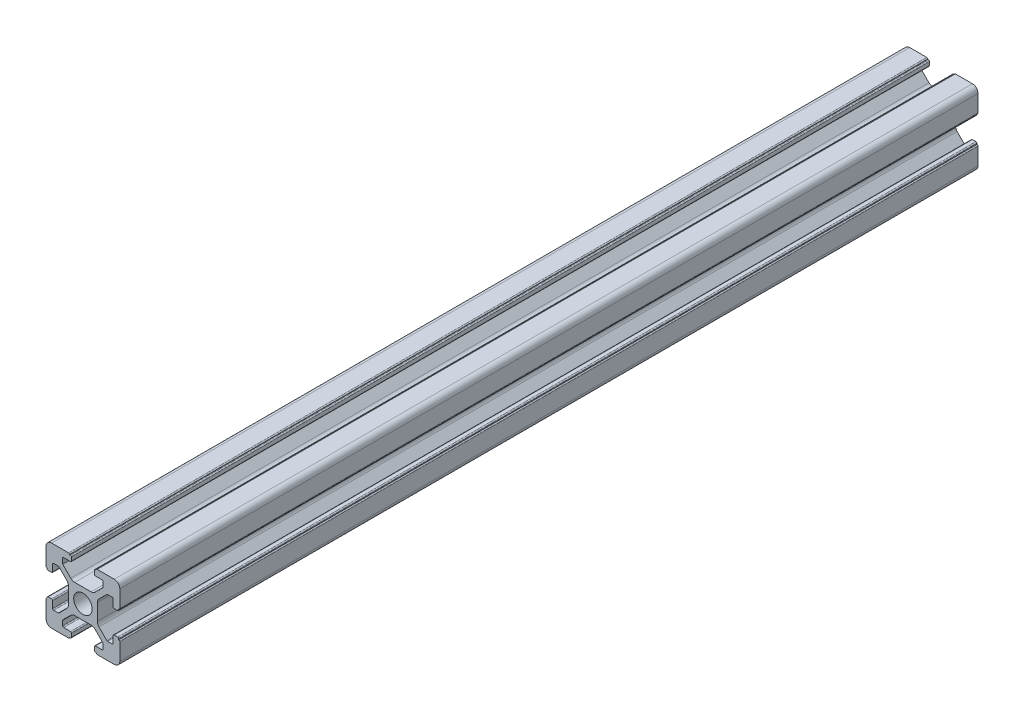
SolidWorks part; units mm, degrees
ref_plane "Alzado" through (0, 0, 0) normal (0, 0, 1) x (1, 0, 0)
ref_plane "Planta" through (0, 0, 0) normal (0, 1, 0) x (1, 0, 0)
ref_plane "Vista lateral" through (0, 0, 0) normal (1, 0, 0) x (0, 0, -1)
sketch "Croquis1" plane through (0, 0, 0) normal (0, 0, 1) x (1, 0, 0)
  point P0 (0, 0)
sketch3d "Croquis3D1"
  line L0 (0, 0, 0) -> (0, 0, 232.5)
  dimension "D1" = 232.5
other "Pg20_t_slot 20X20(1)"
ref_plane "Plano1" through (0, 0, 0) normal (0, 0, 1) x (1, 0, 0)
sketch "Croquis3" plane through (0, 0, 0) normal (0, 0, 1) x (1, 0, 0)
  line L0 (0, 0) -> (0, 10) construction
  line L1 (0, 0) -> (10, 0) construction
  line L2 (-2.218, 3.9) -> (2.218, 3.9)
  line L3 (3.2787, 4.3393) -> (5.418, 6.4787)
  line L4 (5.5, 6.6766) -> (5.5, 7.92)
  line L5 (5.22, 8.2) -> (3.38, 8.2)
  line L6 (3.1, 8.48) -> (3.1, 9.42)
  line L7 (3.88, 10) -> (8.5, 10)
  line L8 (10, 8.5) -> (10, 3.88)
  line L9 (9.42, 3.1) -> (8.48, 3.1)
  line L10 (6.6766, 5.5) -> (7.92, 5.5)
  line L11 (6.4787, 5.418) -> (4.3393, 3.2787)
  line L12 (3.9, 2.218) -> (3.9, -2.218)
  line L13 (0, 10) -> (3.6, 10) construction
  line L14 (10, 3.6) -> (10, 0) construction
  line L15 (0, 0) -> (10, 10) construction
  line L16 (8.2, 5.22) -> (8.2, 3.38)
  line L17 (5.5, 6.5607) -> (6.5607, 5.5) construction
  line L18 (2.8393, 3.9) -> (3.9, 2.8393) construction
  line L19 (3.38, 9.7) -> (3.6, 9.7)
  line L20 (3.6, 9.7) -> (3.6, 9.72)
  line L21 (9.7, 3.38) -> (9.7, 3.6)
  line L22 (9.7, 3.6) -> (9.72, 3.6)
  line L23 (2.8393, 3.9) -> (3.9, 3.9) construction
  line L24 (3.9, 3.9) -> (3.9, 2.8393) construction
  line L25 (6.4787, -5.418) -> (4.3393, -3.2787)
  line L26 (6.6766, -5.5) -> (7.92, -5.5)
  line L27 (8.2, -5.22) -> (8.2, -3.38)
  line L28 (9.42, -3.1) -> (8.48, -3.1)
  line L29 (9.7, -3.6) -> (9.72, -3.6)
  line L30 (9.7, -3.38) -> (9.7, -3.6)
  line L31 (10, -8.5) -> (10, -3.88)
  line L32 (3.88, -10) -> (8.5, -10)
  line L33 (3.6, -9.7) -> (3.6, -9.72)
  line L34 (3.38, -9.7) -> (3.6, -9.7)
  line L35 (3.1, -8.48) -> (3.1, -9.42)
  line L36 (5.22, -8.2) -> (3.38, -8.2)
  line L37 (5.5, -6.6766) -> (5.5, -7.92)
  line L38 (3.2787, -4.3393) -> (5.418, -6.4787)
  line L39 (-2.218, -3.9) -> (2.218, -3.9)
  line L40 (-5.5, -6.6766) -> (-5.5, -7.92)
  line L41 (-5.22, -8.2) -> (-3.38, -8.2)
  line L42 (-3.1, -8.48) -> (-3.1, -9.42)
  line L43 (-3.38, -9.7) -> (-3.6, -9.7)
  line L44 (-3.6, -9.7) -> (-3.6, -9.72)
  line L45 (-3.88, -10) -> (-8.5, -10)
  line L46 (-10, -8.5) -> (-10, -3.88)
  line L47 (-9.7, -3.6) -> (-9.72, -3.6)
  line L48 (-9.7, -3.38) -> (-9.7, -3.6)
  line L49 (-9.42, -3.1) -> (-8.48, -3.1)
  line L50 (-8.2, -5.22) -> (-8.2, -3.38)
  line L51 (-6.6766, -5.5) -> (-7.92, -5.5)
  line L52 (-6.4787, -5.418) -> (-4.3393, -3.2787)
  line L53 (-3.2787, -4.3393) -> (-5.418, -6.4787)
  line L54 (-3.9, 2.218) -> (-3.9, -2.218)
  line L55 (-9.7, 3.6) -> (-9.72, 3.6)
  line L56 (-9.7, 3.38) -> (-9.7, 3.6)
  line L57 (-9.42, 3.1) -> (-8.48, 3.1)
  line L58 (-8.2, 5.22) -> (-8.2, 3.38)
  line L59 (-6.6766, 5.5) -> (-7.92, 5.5)
  line L60 (-6.4787, 5.418) -> (-4.3393, 3.2787)
  line L61 (-3.2787, 4.3393) -> (-5.418, 6.4787)
  line L62 (-10, 8.5) -> (-10, 3.88)
  line L63 (-3.88, 10) -> (-8.5, 10)
  line L64 (-3.6, 9.7) -> (-3.6, 9.72)
  line L65 (-3.38, 9.7) -> (-3.6, 9.7)
  line L66 (-3.1, 8.48) -> (-3.1, 9.42)
  line L67 (-5.22, 8.2) -> (-3.38, 8.2)
  line L68 (-5.5, 6.6766) -> (-5.5, 7.92)
  circle A0 centre (0, 0) radius 2.5
  arc A1 (10, 8.5) -> (8.5, 10) centre (8.5, 8.5) ccw
  arc A2 (3.88, 10) -> (3.6, 9.72) centre (3.88, 9.72) ccw
  arc A3 (3.38, 9.7) -> (3.1, 9.42) centre (3.38, 9.42) ccw
  arc A4 (10, 3.88) -> (9.72, 3.6) centre (9.72, 3.88) cw
  arc A5 (9.7, 3.38) -> (9.42, 3.1) centre (9.42, 3.38) cw
  arc A6 (8.2, 5.22) -> (7.92, 5.5) centre (7.92, 5.22) ccw
  arc A7 (5.22, 8.2) -> (5.5, 7.92) centre (5.22, 7.92) cw
  arc A8 (3.1, 8.48) -> (3.38, 8.2) centre (3.38, 8.48) ccw
  arc A9 (8.48, 3.1) -> (8.2, 3.38) centre (8.48, 3.38) cw
  arc A10 (4.3393, 3.2787) -> (3.9, 2.218) centre (5.4, 2.218) ccw
  arc A11 (3.2787, 4.3393) -> (2.218, 3.9) centre (2.218, 5.4) cw
  arc A12 (6.4787, 5.418) -> (6.6766, 5.5) centre (6.6766, 5.22) cw
  arc A13 (5.5, 6.6766) -> (5.418, 6.4787) centre (5.22, 6.6766) cw
  arc A14 (4.3393, -3.2787) -> (3.9, -2.218) centre (5.4, -2.218) cw
  arc A15 (6.4787, -5.418) -> (6.6766, -5.5) centre (6.6766, -5.22) ccw
  arc A16 (8.2, -5.22) -> (7.92, -5.5) centre (7.92, -5.22) cw
  arc A17 (8.48, -3.1) -> (8.2, -3.38) centre (8.48, -3.38) ccw
  arc A18 (9.7, -3.38) -> (9.42, -3.1) centre (9.42, -3.38) ccw
  arc A19 (10, -3.88) -> (9.72, -3.6) centre (9.72, -3.88) ccw
  arc A20 (10, -8.5) -> (8.5, -10) centre (8.5, -8.5) cw
  arc A21 (3.88, -10) -> (3.6, -9.72) centre (3.88, -9.72) cw
  arc A22 (3.38, -9.7) -> (3.1, -9.42) centre (3.38, -9.42) cw
  arc A23 (3.1, -8.48) -> (3.38, -8.2) centre (3.38, -8.48) cw
  arc A24 (5.22, -8.2) -> (5.5, -7.92) centre (5.22, -7.92) ccw
  arc A25 (5.5, -6.6766) -> (5.418, -6.4787) centre (5.22, -6.6766) ccw
  arc A26 (3.2787, -4.3393) -> (2.218, -3.9) centre (2.218, -5.4) ccw
  arc A27 (-5.5, -6.6766) -> (-5.418, -6.4787) centre (-5.22, -6.6766) cw
  arc A28 (-5.22, -8.2) -> (-5.5, -7.92) centre (-5.22, -7.92) cw
  arc A29 (-3.1, -8.48) -> (-3.38, -8.2) centre (-3.38, -8.48) ccw
  arc A30 (-3.38, -9.7) -> (-3.1, -9.42) centre (-3.38, -9.42) ccw
  arc A31 (-3.88, -10) -> (-3.6, -9.72) centre (-3.88, -9.72) ccw
  arc A32 (-10, -8.5) -> (-8.5, -10) centre (-8.5, -8.5) ccw
  arc A33 (-10, -3.88) -> (-9.72, -3.6) centre (-9.72, -3.88) cw
  arc A34 (-9.7, -3.38) -> (-9.42, -3.1) centre (-9.42, -3.38) cw
  arc A35 (-8.48, -3.1) -> (-8.2, -3.38) centre (-8.48, -3.38) cw
  arc A36 (-8.2, -5.22) -> (-7.92, -5.5) centre (-7.92, -5.22) ccw
  arc A37 (-6.4787, -5.418) -> (-6.6766, -5.5) centre (-6.6766, -5.22) cw
  arc A38 (-3.2787, -4.3393) -> (-2.218, -3.9) centre (-2.218, -5.4) cw
  arc A39 (-4.3393, -3.2787) -> (-3.9, -2.218) centre (-5.4, -2.218) ccw
  arc A40 (-3.2787, 4.3393) -> (-2.218, 3.9) centre (-2.218, 5.4) ccw
  arc A41 (-4.3393, 3.2787) -> (-3.9, 2.218) centre (-5.4, 2.218) cw
  arc A42 (-10, 3.88) -> (-9.72, 3.6) centre (-9.72, 3.88) ccw
  arc A43 (-9.7, 3.38) -> (-9.42, 3.1) centre (-9.42, 3.38) ccw
  arc A44 (-8.48, 3.1) -> (-8.2, 3.38) centre (-8.48, 3.38) ccw
  arc A45 (-8.2, 5.22) -> (-7.92, 5.5) centre (-7.92, 5.22) cw
  arc A46 (-6.4787, 5.418) -> (-6.6766, 5.5) centre (-6.6766, 5.22) ccw
  arc A47 (-5.5, 6.6766) -> (-5.418, 6.4787) centre (-5.22, 6.6766) ccw
  arc A48 (-10, 8.5) -> (-8.5, 10) centre (-8.5, 8.5) cw
  arc A49 (-3.88, 10) -> (-3.6, 9.72) centre (-3.88, 9.72) cw
  arc A50 (-3.38, 9.7) -> (-3.1, 9.42) centre (-3.38, 9.42) cw
  arc A51 (-3.1, 8.48) -> (-3.38, 8.2) centre (-3.38, 8.48) cw
  arc A52 (-5.22, 8.2) -> (-5.5, 7.92) centre (-5.22, 7.92) ccw
  point P9 (0, 0)
  point P106 (3.9, 0)
  point P145 (0, -3.9)
  point P148 (0, 3.9)
  dimension "D1" = 5
  dimension "D8" = 1.5
  dimension "D15" = 0.28
  dimension "D19" = 0.28
  dimension "D20" = 1.5
  dimension "D21" = 0.28
  dimension "D2" = 10
  dimension "D3" = 10
  dimension "D4" = 0.75
  dimension "D5" = 0.75
  dimension "D6" = 3.1
  dimension "D7" = 3.1
  dimension "D9" = 1.8
  dimension "D10" = 1.8
  dimension "D11" = 3.6
  dimension "D12" = 3.6
  dimension "D13" = 0.3
  dimension "D14" = 0.3
  dimension "D16" = 3.9
  dimension "D17" = 5.5
  dimension "D18" = 5.5
